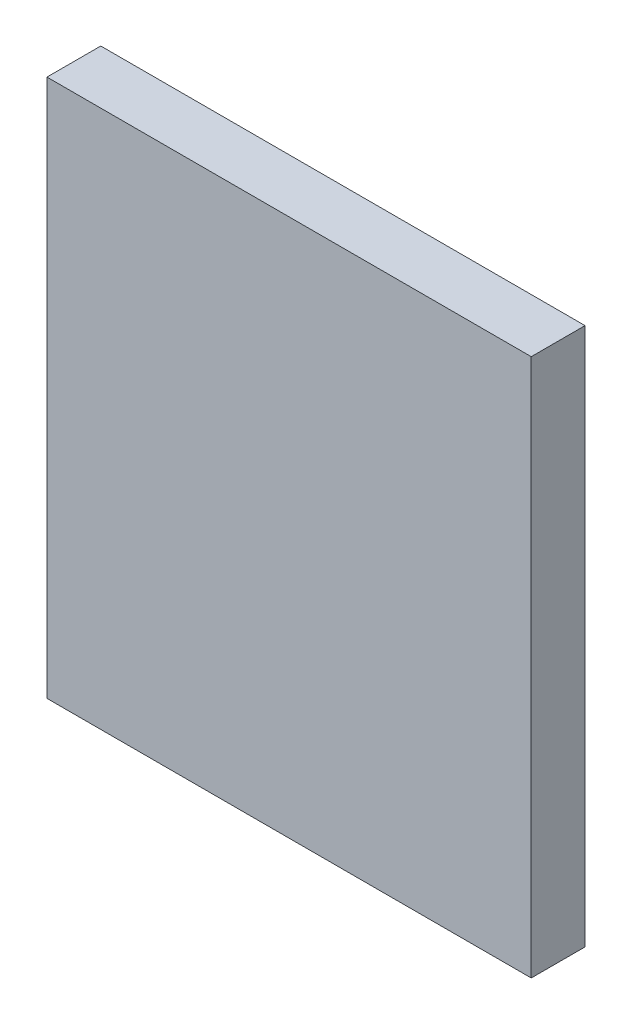
SolidWorks part; units mm, degrees
ref_plane "Front Plane" through (0, 0, 0) normal (0, 0, 1) x (1, 0, 0)
ref_plane "Top Plane" through (0, 0, 0) normal (0, 1, 0) x (1, 0, 0)
ref_plane "Right Plane" through (0, 0, 0) normal (1, 0, 0) x (0, 0, -1)
sketch "Sketch1" plane through (0, 0, 0) normal (0, 0, 1) x (1, 0, 0)
  line L1 (-45, 50) -> (45, 50)
  line L2 (-45, 50) -> (-45, -50)
  line L3 (-45, -50) -> (45, -50)
  line L4 (45, 50) -> (45, -50)
  line L5 (-45, 50) -> (45, -50) construction
  line L6 (-45, -50) -> (45, 50) construction
  point P0 (0, 0)
  dimension "D1" = 90
  dimension "D2" = 100
extrude "Boss-Extrude1" add sketch "Sketch1" against normal blind 2
sketch "Sketch2" plane through (0, 0, -2) normal (0, 0, -1) x (-1, 0, 0)
  line L0 (-45, 50) -> (45, 50)
  line L1 (45, 50) -> (45, -50)
  line L2 (45, -50) -> (-45, -50)
  line L3 (-45, -50) -> (-45, 50)
  line L4 (-40, -45) -> (-40, 45)
  line L5 (-40, 45) -> (40, 45)
  line L6 (40, 45) -> (40, -45)
  line L7 (40, -45) -> (-40, -45)
  line L8 (-40, 45) -> (-45, 45)
  line L9 (-45, 45) -> (-45, 50)
  line L10 (-40, 45) -> (-40, 50)
  line L11 (-40, 50) -> (-45, 50)
  line L12 (45, 50) -> (40, 50)
  line L13 (40, 50) -> (40, 45)
  line L14 (45, 45) -> (45, 50)
  line L15 (40, 50) -> (45, 50)
  line L16 (45, 45) -> (40, 45)
  line L17 (-40, -45) -> (-45, -45)
  line L18 (-45, -45) -> (-45, -50)
  line L19 (-40, -50) -> (-40, -45)
  line L20 (40, -45) -> (40, -50)
  line L21 (40, -50) -> (45, -50)
  line L22 (40, -45) -> (45, -45)
  line L23 (45, -45) -> (45, -50)
  line L24 (-40, 50) -> (-45, 50)
  line L25 (-45, 50) -> (-45, 45)
  line L26 (-40, 45) -> (-45, 45)
  line L27 (-40, 50) -> (-40, 45)
  line L28 (-42.5, 45) -> (-42.5, 47.5)
  line L29 (42.5, 45) -> (42.5, 47.5)
  line L30 (40, -47.5) -> (42.5, -47.5)
  line L31 (-40, -47.5) -> (-42.5, -47.5)
  line L32 (45, -45) -> (44.5, -45)
  line L33 (-40, -50) -> (-45, -50)
  line L34 (-40, -50) -> (-40, -45)
  line L35 (-40, -45) -> (-45, -45)
  line L36 (-45, -50) -> (-45, -45)
  line L37 (-45, -45) -> (-45, -45.5)
  line L38 (-45, -45) -> (-44.5, -45)
  line L39 (-40, 45) -> (-45, 45)
  line L40 (-40, 45) -> (-40, 50)
  line L41 (-40, 50) -> (-45, 50)
  line L42 (-45, 45) -> (-45, 50)
  line L43 (-40, 45) -> (-45, 50) construction
  line L44 (-40, 50) -> (-45, 45) construction
  line L45 (45, 45) -> (40, 45)
  line L46 (45, 45) -> (45, 50)
  line L47 (45, 50) -> (40, 50)
  line L48 (40, 45) -> (40, 50)
  line L49 (45, 45) -> (40, 50) construction
  line L50 (45, 50) -> (40, 45) construction
  line L51 (40, -50) -> (45, -50)
  line L52 (40, -50) -> (40, -45)
  line L53 (40, -45) -> (45, -45)
  line L54 (45, -50) -> (45, -45)
  line L55 (45, -45) -> (45, -45.5)
  line L56 (-45, 0) -> (-40, 0)
  line L57 (40.5, -49.5) -> (44.5, -49.5)
  line L58 (40.5, -49.5) -> (40.5, -45.5)
  line L59 (40.5, -45.5) -> (44.5, -45.5)
  line L60 (44.5, -49.5) -> (44.5, -45.5)
  line L61 (40.5, -49.5) -> (44.5, -45.5) construction
  line L62 (40.5, -45.5) -> (44.5, -49.5) construction
  line L63 (-40.5, -49.5) -> (-44.5, -49.5)
  line L64 (-40.5, -49.5) -> (-40.5, -45.5)
  line L65 (-40.5, -45.5) -> (-44.5, -45.5)
  line L66 (-44.5, -49.5) -> (-44.5, -45.5)
  line L67 (-40.5, -49.5) -> (-44.5, -45.5) construction
  line L68 (-40.5, -45.5) -> (-44.5, -49.5) construction
  line L69 (40.5, 45.5) -> (44.5, 45.5)
  line L70 (44.5, 49.5) -> (44.5, 45.5)
  line L71 (40.5, 49.5) -> (44.5, 49.5)
  line L72 (40.5, 49.5) -> (40.5, 45.5)
  line L73 (-40.5, 45.5) -> (-44.5, 45.5)
  line L74 (-44.5, 49.5) -> (-44.5, 45.5)
  line L75 (-40.5, 49.5) -> (-44.5, 49.5)
  line L76 (-40.5, 49.5) -> (-40.5, 45.5)
  dimension "D1" = 5
extrude "Boss-Extrude2" add sketch "Sketch2" along normal blind 8
sketch "Sketch3" plane through (0, 0, -10) normal (0, 0, -1) x (-1, 0, 0)
  line L0 (-44.5, 49.5) -> (-40.5, 49.5)
  line L1 (-40.5, 49.5) -> (-40.5, 45.5)
  line L2 (-40.5, 45.5) -> (-44.5, 45.5)
  line L3 (-44.5, 45.5) -> (-44.5, 49.5)
  line L4 (44.5, 45.5) -> (40.5, 45.5)
  line L5 (40.5, 45.5) -> (40.5, 49.5)
  line L6 (40.5, 49.5) -> (44.5, 49.5)
  line L7 (44.5, 49.5) -> (44.5, 45.5)
  line L8 (40.5, -45.5) -> (44.5, -45.5)
  line L9 (44.5, -45.5) -> (44.5, -49.5)
  line L10 (44.5, -49.5) -> (40.5, -49.5)
  line L11 (40.5, -49.5) -> (40.5, -45.5)
  line L12 (-40.5, -49.5) -> (-44.5, -49.5)
  line L13 (-44.5, -49.5) -> (-44.5, -45.5)
  line L14 (-44.5, -45.5) -> (-40.5, -45.5)
  line L15 (-40.5, -45.5) -> (-40.5, -49.5)
extrude "Cut-Extrude2" cut sketch "Sketch3" against normal blind 3
